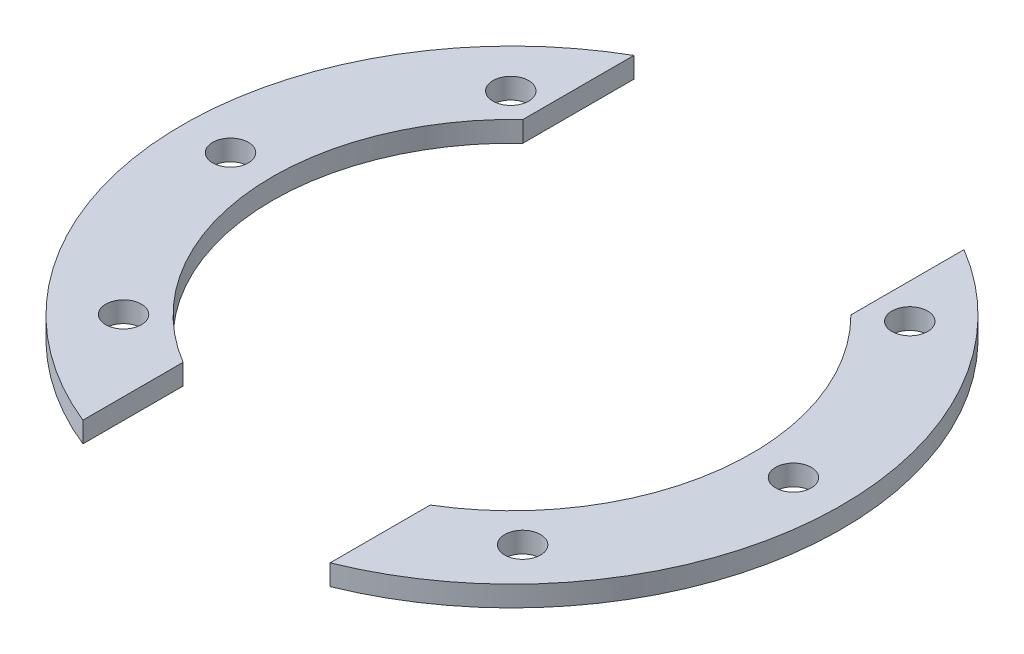
SolidWorks part; units mm, degrees
ref_plane "Front" through (0, 0, 0) normal (0, 0, 1) x (1, 0, 0)
ref_plane "Top" through (0, 0, 0) normal (0, 1, 0) x (1, 0, 0)
ref_plane "Right" through (0, 0, 0) normal (1, 0, 0) x (0, 0, -1)
sketch "草图1" plane through (0, 0, 0) normal (0, 1, 0) x (1, 0, 0)
  line L0 (0, 0) -> (37.4593, 0) construction
  line L1 (0, 0) -> (0, -33.86) construction
  line L2 (12.3277, 12.3557) -> (12.3277, 20.5919)
  line L3 (-11.94, 12.7308) -> (-11.94, 20.8192)
  line L4 (4, -23.6643) -> (4, -25.6905)
  line L5 (5.349, 23.3963) -> (5.349, 25.4438)
  line L6 (-5.349, 23.3963) -> (-5.349, 25.4438)
  line L7 (-4, -23.6643) -> (-4, -25.6905)
  line L8 (9, -22.2486) -> (9, -14.9544)
  line L9 (-9, -22.2486) -> (-9, -14.9544)
  line L11 (-7.5, 7.5) -> (7.5, 7.5)
  line L12 (-7.5, 7.5) -> (-7.5, -7.5)
  line L13 (-7.5, -7.5) -> (7.5, -7.5)
  line L14 (7.5, 7.5) -> (7.5, -7.5)
  line L15 (-7.5, 7.5) -> (7.5, -7.5) construction
  line L16 (-7.5, -7.5) -> (7.5, 7.5) construction
  circle A0 centre (0, 0) radius 24
  circle A1 centre (14.872, 14.097) radius 1.3
  circle A2 centre (14.872, -14.097) radius 1.3
  circle A3 centre (-14.187, 14.1) radius 1.3
  circle A4 centre (-14.187, -14.1) radius 1.3
  circle A5 centre (-20.498, 0) radius 1.3
  circle A6 centre (20.498, 0) radius 1.3
  circle A7 centre (0, 0) radius 26
  arc A8 (12.3277, 12.3557) -> (-11.94, 12.7308) centre (0, 0) cw
  arc A9 (-11.94, 20.8192) -> (12.3277, 20.5919) centre (0, 0) ccw
  arc A10 (-5.349, 25.4438) -> (5.349, 25.4438) centre (0, 0) cw
  arc A11 (-5.349, 23.3963) -> (5.349, 23.3963) centre (0, 0) cw
  circle A12 centre (-14.187, 14.1) radius 2.3
  circle A13 centre (-20.498, 0) radius 2.3
  circle A14 centre (-14.187, -14.1) radius 2.3
  circle A15 centre (14.872, -14.097) radius 2.3
  circle A16 centre (20.498, 0) radius 2.3
  circle A17 centre (14.872, 14.097) radius 2.3
  circle A18 centre (0, -15) radius 1.6
  arc A19 (4, -23.6643) -> (-4, -23.6643) centre (0, 0) cw
  arc A20 (4, -25.6905) -> (-4, -25.6905) centre (0, 0) cw
  arc A21 (9, -14.9544) -> (-9, -14.9544) centre (0, 0) cw
  arc A22 (9, -22.2486) -> (-9, -22.2486) centre (0, 0) cw
  circle A23 centre (0, 15) radius 1.6
  circle A24 centre (15, 0) radius 1.6
  circle A25 centre (-15, 0) radius 1.6
  point P27 (0, 24)
  dimension "D1" = 48
  dimension "D4" = 2.6
  dimension "D7" = 20.498
  dimension "D8" = 52
  dimension "D9" = 4.6
  dimension "D2" = 14.097
  dimension "D3" = 14.872
  dimension "D5" = 14.187
  dimension "D6" = 14.1
  dimension "D10" = 15
  dimension "D11" = 8
  dimension "D12" = 18
  dimension "D13" = 15
  dimension "D14" = 15
  dimension "D15" = 15
extrude "凸台-拉伸1" add sketch "草图1" along normal blind 1.5 contours A12 L3 A0 L9 A8 A14 A13 | L2 A8 L8 A0 A17 A16 A15 | L3 A12 A3 | A13 A5 | A14 A4 | A16 A6 | A17 A1 | A15 A2
